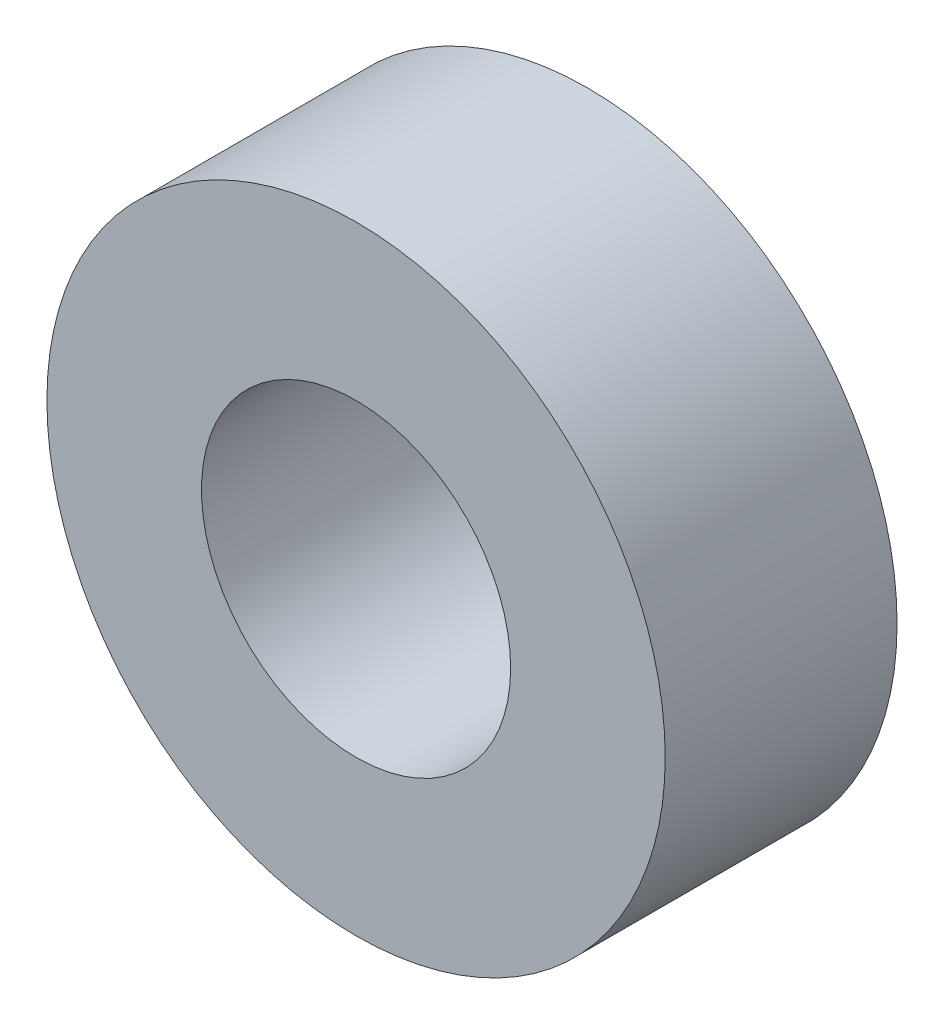
SolidWorks part; units mm, degrees
ref_plane "前视基准面" through (0, 0, 0) normal (0, 0, 1) x (1, 0, 0)
ref_plane "上视基准面" through (0, 0, 0) normal (0, 1, 0) x (1, 0, 0)
ref_plane "右视基准面" through (0, 0, 0) normal (1, 0, 0) x (0, 0, -1)
other "Configuration Table"
sketch "草图1" plane through (0, 0, 0) normal (0, 0, 1) x (1, 0, 0)
  circle A0 centre (0, 0) radius 2
  circle A1 centre (0, 0) radius 4
  dimension "D1" = 4
  dimension "D2" = 8
extrude "凸台-拉伸1" add sketch "草图1" along normal blind 3
